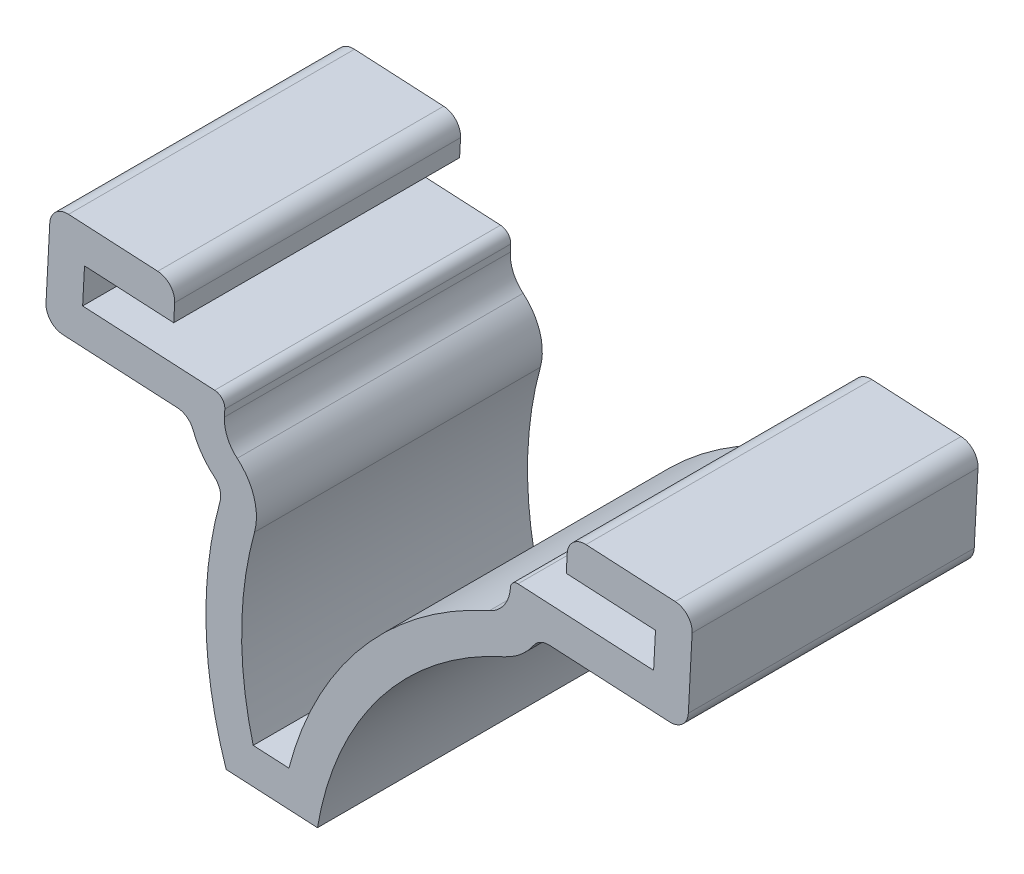
SolidWorks part; units mm, degrees
ref_plane "Plan de face" through (0, 0, 0) normal (0, 0, 1) x (1, 0, 0)
ref_plane "Plan de dessus" through (0, 0, 0) normal (0, 1, 0) x (1, 0, 0)
ref_plane "Plan de droite" through (0, 0, 0) normal (1, 0, 0) x (0, 0, -1)
sketch "Esquisse1" plane through (0, 0, 0) normal (0, 0, 1) x (1, 0, 0)
  line L0 (-30.0673, 113.1777) -> (-23.077, 112.8089) construction
  line L1 (-30.0146, 114.1764) -> (-30.0673, 113.1777) construction
  line L2 (-30.0146, 114.1764) -> (-23.0243, 113.8075) construction
  line L3 (-21.0271, 113.7022) -> (-14.0368, 113.3333) construction
  line L4 (-14.0368, 113.3333) -> (-14.0895, 112.3347) construction
  line L5 (-21.0798, 112.7035) -> (-14.0895, 112.3347) construction
  line L6 (-18.0946, 112.3437) -> (-18.0839, 112.5455) construction
  line L7 (-25.294, 104.9148) -> (-24.2953, 104.8621) construction
  line L8 (-26.0728, 112.967) -> (-26.0992, 112.4677) construction
  line L9 (-30.0673, 113.1777) -> (-26.3724, 112.9828)
  line L10 (-30.0146, 114.1764) -> (-30.0673, 113.1777)
  line L11 (-30.0146, 114.1764) -> (-27.518, 114.0446)
  line L12 (-16.5333, 113.4651) -> (-14.0368, 113.3333)
  line L13 (-14.0368, 113.3333) -> (-14.0895, 112.3347)
  line L14 (-17.8842, 112.5349) -> (-14.0895, 112.3347)
  line L15 (-18.0946, 112.3437) -> (-18.0945, 112.3458)
  line L16 (-25.294, 104.9148) -> (-24.2953, 104.8621)
  line L17 (-26.0886, 112.6674) -> (-26.0992, 112.4677)
  line L18 (-27.4917, 114.5439) -> (-27.518, 114.0446)
  line L19 (-16.507, 113.9644) -> (-16.5333, 113.4651)
  line L20 (-30.9868, 114.7283) -> (-31.0922, 112.7311)
  line L21 (-13.0118, 113.78) -> (-13.1172, 111.7827)
  line L23 (-26.0509, 103.9533) -> (-23.4955, 103.8185)
  line L25 (-30.6193, 112.2055) -> (-27.415, 112.0364)
  line L26 (-17.0015, 111.487) -> (-13.6429, 111.3098)
  line L27 (-30.4612, 115.2013) -> (-27.9647, 115.0696)
  line L28 (-15.9813, 114.4373) -> (-13.4848, 114.3056)
  arc A0 (-18.6862, 111.483) -> (-18.0946, 112.3437) centre (-19.0932, 112.3964) ccw construction
  arc A1 (-18.6862, 111.483) -> (-24.2953, 104.8621) centre (-14.6164, 102.3486) ccw construction
  arc A2 (-25.2578, 110.098) -> (-25.294, 104.9148) centre (-15.6178, 107.4391) ccw construction
  arc A3 (-25.2578, 110.098) -> (-25.7419, 111.6477) centre (-26.7038, 110.4968) ccw construction
  arc A4 (-26.0992, 112.4677) -> (-25.7419, 111.6477) centre (-25.1005, 112.415) ccw construction
  arc A5 (-18.6862, 111.483) -> (-18.0946, 112.3437) centre (-19.0932, 112.3964) ccw
  arc A6 (-18.6862, 111.483) -> (-24.2953, 104.8621) centre (-14.6164, 102.3486) ccw
  arc A7 (-25.2578, 110.098) -> (-25.294, 104.9148) centre (-15.6178, 107.4391) ccw
  arc A8 (-25.2578, 110.098) -> (-25.7419, 111.6477) centre (-26.7038, 110.4968) ccw
  arc A9 (-26.0992, 112.4677) -> (-25.7419, 111.6477) centre (-25.1005, 112.415) ccw
  arc A10 (-26.0886, 112.6674) -> (-26.3724, 112.9828) centre (-26.3882, 112.6832) ccw
  arc A11 (-17.8842, 112.5349) -> (-18.0945, 112.3458) centre (-17.8947, 112.3352) ccw
  arc A12 (-26.9732, 111.7127) -> (-26.3832, 110.8804) centre (-25.1005, 112.415) ccw
  arc A13 (-26.2218, 110.3639) -> (-26.3832, 110.8804) centre (-26.7038, 110.4968) ccw
  arc A14 (-26.2218, 110.3639) -> (-26.0509, 103.9533) centre (-15.6178, 107.4391) ccw
  arc A15 (-18.2792, 110.5695) -> (-23.4955, 103.8185) centre (-14.6164, 102.3486) ccw
  arc A16 (-18.2792, 110.5695) -> (-17.4409, 111.2694) centre (-19.0932, 112.3964) ccw
  arc A17 (-30.9868, 114.7283) -> (-30.4612, 115.2013) centre (-30.4875, 114.702) cw
  arc A18 (-27.9647, 115.0696) -> (-27.4917, 114.5439) centre (-27.991, 114.5703) cw
  arc A19 (-30.6193, 112.2055) -> (-31.0922, 112.7311) centre (-30.5929, 112.7048) cw
  arc A20 (-16.507, 113.9644) -> (-15.9813, 114.4373) centre (-16.0077, 113.938) cw
  arc A21 (-13.0118, 113.78) -> (-13.4848, 114.3056) centre (-13.5111, 113.8063) ccw
  arc A22 (-13.6429, 111.3098) -> (-13.1172, 111.7827) centre (-13.6165, 111.8091) ccw
  arc A23 (-17.4409, 111.2694) -> (-17.0015, 111.487) centre (-17.0279, 110.9877) cw
  arc A24 (-27.415, 112.0364) -> (-26.9732, 111.7127) centre (-27.4413, 111.5371) cw
  dimension "D5" = 0.3
  dimension "D6" = 0.2
  dimension "D12" = 0.5
  dimension "D13" = 0.5
  dimension "D1" = 1
  dimension "D2" = 3.5
  dimension "D3" = 1
  dimension "D4" = 3.5
  dimension "D8" = 1
  dimension "D9" = 1
  dimension "D10" = 1
  dimension "D11" = 1
  dimension "D7" = 1
extrude "Extrusion1" add sketch "Esquisse1" along normal blind 8
